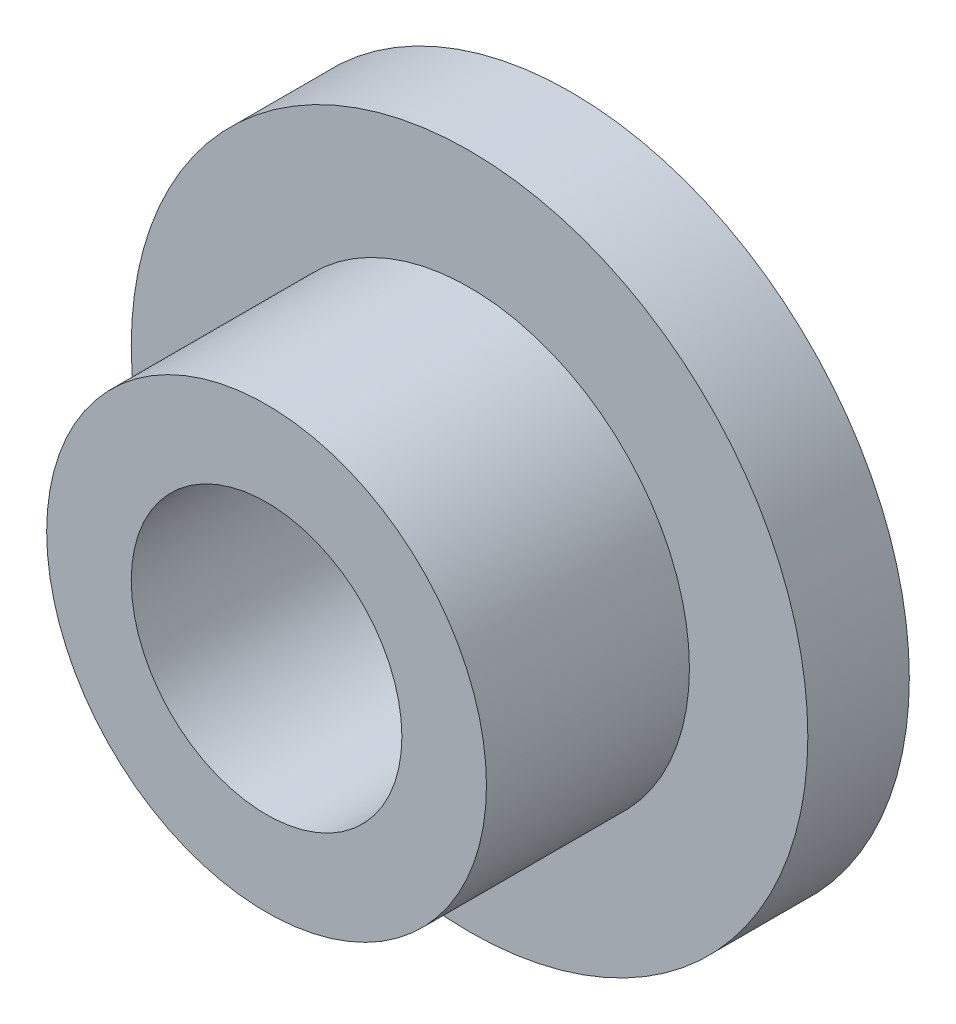
SolidWorks part; units mm, degrees
ref_plane "Front Plane" through (0, 0, 0) normal (0, 0, 1) x (1, 0, 0)
ref_plane "Top Plane" through (0, 0, 0) normal (0, 1, 0) x (1, 0, 0)
ref_plane "Right Plane" through (0, 0, 0) normal (1, 0, 0) x (0, 0, -1)
sketch "Sketch1" plane through (0, 0, 0) normal (0, 0, 1) x (1, 0, 0)
  circle A0 centre (-25.8192, 38.9769) radius 1.3
  circle A1 centre (-25.8192, 38.9769) radius 0.8
  circle A6 centre (-25.8192, 38.9769) radius 0.7 construction
  circle A7 centre (-25.8192, 38.9769) radius 1.5 construction
  dimension "D1" = 1.6
  dimension "D2" = 0.2
extrude "Boss-Extrude1" add sketch "Sketch1" along normal blind 1.2
sketch "Sketch2" plane through (0, 0, 0) normal (0, 0, -1) x (-1, 0, 0)
  circle A0 centre (25.8192, 38.9769) radius 2
  circle A1 centre (25.8192, 38.9769) radius 0.8
  dimension "D1" = 4
extrude "Boss-Extrude2" add sketch "Sketch2" along normal blind 0.6
